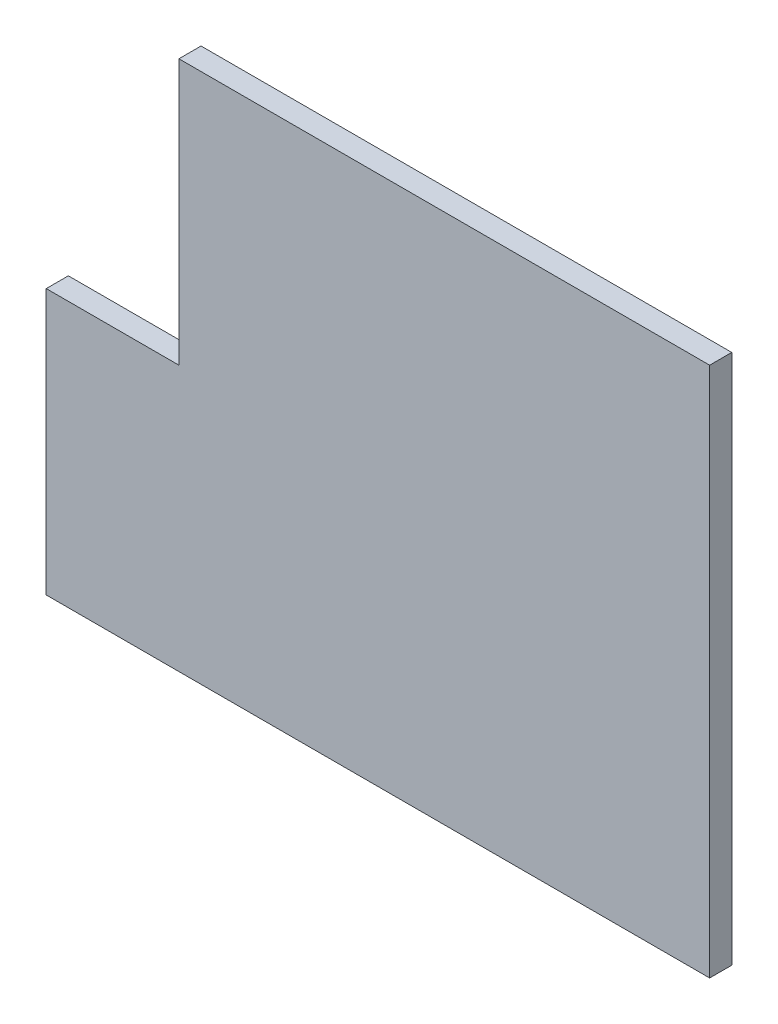
SolidWorks part; units mm, degrees
material "ASTM A36 Steel"
ref_plane "Front Plane" through (0, 0, 0) normal (0, 0, 1) x (1, 0, 0)
ref_plane "Top Plane" through (0, 0, 0) normal (0, 1, 0) x (1, 0, 0)
ref_plane "Right Plane" through (0, 0, 0) normal (1, 0, 0) x (0, 0, -1)
sketch "Sketch1" plane through (0, 0, 0) normal (0, 0, 1) x (1, 0, 0)
  line L0 (-72.0209, 0) -> (72.0209, 0) construction
  line L1 (0, -54.8965) -> (0, 54.8965) construction
  line L3 (-47.625, -38.1) -> (47.625, -38.1)
  line L4 (-47.625, -38.1) -> (-47.625, 38.1)
  line L5 (-47.625, 38.1) -> (47.625, 38.1)
  line L6 (47.625, -38.1) -> (47.625, 38.1)
  line L7 (-47.625, -38.1) -> (47.625, 38.1) construction
  line L8 (-47.625, 38.1) -> (47.625, -38.1) construction
  point P0 (0, 0)
  point P4 (0, 0)
  point P8 (0, 0)
  dimension "D1" = 76.2
  dimension "D2" = 95.25
extrude "Boss-Extrude1" add sketch "Sketch1" along normal mid plane 3.175
sketch "Sketch2" plane through (0, 0, 1.5875) normal (0, 0, 1) x (1, 0, 0)
  line L0 (-72.3801, 0) -> (72.3801, 0) construction
  line L1 (0, -50.8317) -> (0, 50.8317) construction
  line L2 (-47.625, 0) -> (-28.575, 0)
  line L3 (-47.625, 38.1) -> (-47.625, -38.1) construction
  line L4 (-28.575, 0) -> (-28.575, 38.1)
  line L5 (47.625, 38.1) -> (-47.625, 38.1) construction
  line L6 (-28.575, 38.1) -> (-47.625, 38.1)
  line L7 (-47.625, 38.1) -> (-47.625, 0)
  point P4 (0, 0)
  point P8 (0, 0)
  line M3 (47.625, 38.1) -> (-47.625, 38.1)
  line M4 (-47.625, 38.1) -> (-47.625, -38.1)
  dimension "D1" = 19.05
extrude "Cut-Extrude1" cut sketch "Sketch2" against normal blind 3.175 contours L2 L4 M3 M4
